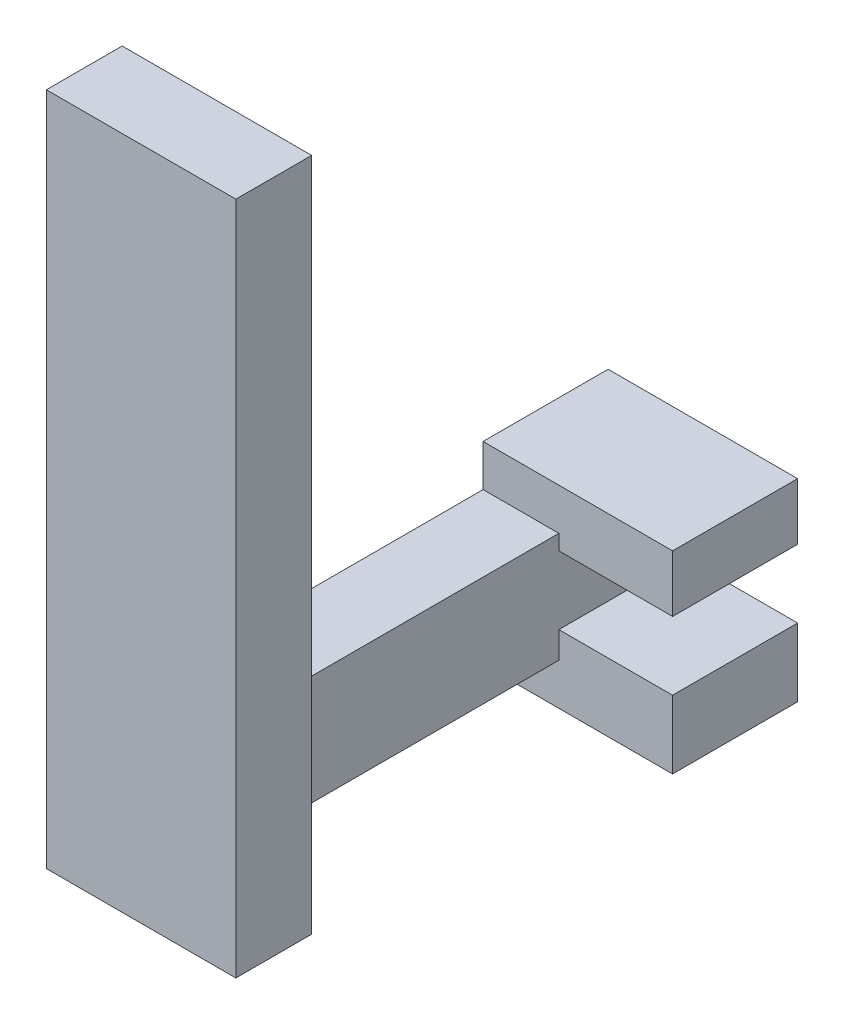
SolidWorks part; units mm, degrees
ref_plane "前视基准面" through (0, 0, 0) normal (0, 0, 1) x (1, 0, 0)
ref_plane "上视基准面" through (0, 0, 0) normal (0, 1, 0) x (1, 0, 0)
ref_plane "右视基准面" through (0, 0, 0) normal (1, 0, 0) x (0, 0, -1)
other "Configuration Table"
sketch "草图1" plane through (0, 0, 0) normal (0, 1, 0) x (1, 0, 0)
  line L1 (-1, -6) -> (1, -6)
  line L2 (-1, -6) -> (-1, 6)
  line L3 (-1, 6) -> (1, 6)
  line L4 (1, -6) -> (1, 6)
  dimension "D1" = 2
  dimension "D2" = 6
  dimension "D3" = 6
  dimension "D4" = 1
extrude "凸台-拉伸1" add sketch "草图1" along normal blind 2.9
sketch "草图2" plane through (1, 0, 0) normal (1, 0, 0) x (0, 0, -1)
  line L0 (6, 2.9) -> (6, 0) construction
  line L1 (2.7, 2.5) -> (6, 2.5)
  line L2 (2.7, 2.5) -> (2.7, 4)
  line L3 (2.7, 4) -> (6, 4)
  line L4 (6, 2.5) -> (6, 4)
  line L5 (-6, 2.9) -> (6, 2.9) construction
  line L6 (-6, 0) -> (6, 0) construction
  line L7 (6, 0.7) -> (2.7, 0.7)
  line L8 (6, 0.7) -> (6, -1.1)
  line L9 (6, -1.1) -> (2.7, -1.1)
  line L10 (2.7, 0.7) -> (2.7, -1.1)
  dimension "D1" = 3.3
  dimension "D2" = 0.4
  dimension "D3" = 1.1
  dimension "D4" = 0.7
  dimension "D5" = 1.1
extrude "凸台-拉伸2" add sketch "草图2" against normal up to surface (57.4 mm away) from offset 3
sketch "草图3" plane through (-1, 0, 0) normal (-1, 0, 0) x (0, 0, 1)
  line L1 (-2.7, 2.9) -> (7.825, 2.9)
  line L2 (-2.7, 2.9) -> (-2.7, 0)
  line L3 (-2.7, 0) -> (7.825, 0)
  line L4 (7.825, 2.9) -> (7.825, 0)
  line L10 (-2.7, 2.9) -> (6, 2.9) construction
  line L11 (-2.7, 0) -> (6, 0) construction
  line L12 (-2.7, 2.9) -> (-2.7, 4) construction
  dimension "D3" = 10.525
extrude "凸台-拉伸3" add sketch "草图3" against normal blind 2
sketch "草图5" plane through (0, 2.9, 0) normal (0, 1, 0) x (1, 0, 0)
  line L1 (-1, -7.825) -> (4, -7.825)
  line L2 (-1, -7.825) -> (-1, -6.825)
  line L3 (-1, -6.825) -> (4, -6.825)
  line L4 (4, -7.825) -> (4, -6.825)
  line L5 (-1, -7.825) -> (4, -7.825)
  line L6 (-1, -7.825) -> (-1, -8.825)
  line L7 (-1, -8.825) -> (4, -8.825)
  line L8 (4, -7.825) -> (4, -8.825)
  point P7 (-0.5, -7.4781)
  point P8 (-0.1409, -7.9519)
  dimension "D1" = 1
  dimension "D2" = 5
  dimension "D3" = 1
extrude "凸台-拉伸5" add sketch "草图5" along normal blind 17.8 from surface at -2.9 contours L2 L3 L4 L1 | L6 L7 L8 L5 starting at face at (0, 0, 2.5625)
